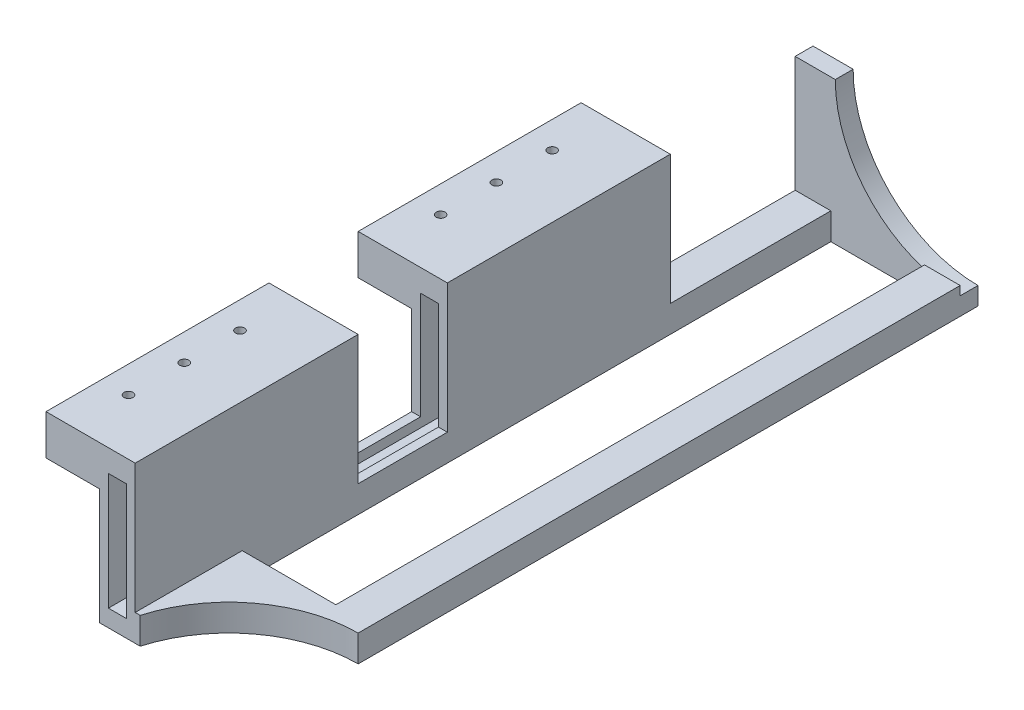
SolidWorks part; units mm, degrees
ref_plane "Alzado" through (0, 0, 0) normal (0, 0, 1) x (1, 0, 0)
ref_plane "Planta" through (0, 0, 0) normal (0, 1, 0) x (1, 0, 0)
ref_plane "Vista lateral" through (0, 0, 0) normal (1, 0, 0) x (0, 0, -1)
sketch "Croquis2" plane through (0, 0, 0) normal (0, 0, 1) x (1, 0, 0)
  line L0 (-4.5963, 11.5024) -> (-4.5963, -1.4976)
  line L1 (-8.5963, 11.5024) -> (-4.5963, 11.5024)
  line L2 (-8.5963, 11.5024) -> (-8.5963, -4.4976)
  line L3 (-8.5963, -4.4976) -> (-4.5963, -4.4976)
  line L9 (-4.5963, -4.4976) -> (9.9037, -4.4976)
  line L11 (-4.5963, -1.4976) -> (9.9037, -1.4976)
  line L12 (9.9037, -4.4976) -> (9.9037, -1.4976)
  dimension "D1" = 13
  dimension "D5" = 3
extrude "Saliente-Extruir1" add sketch "Croquis2" along normal blind 82
sketch "Croquis3" plane through (0, 11.5024, 0) normal (0, 1, 0) x (1, 0, 0)
  line L0 (-4.5963, -82) -> (-4.5963, 0) construction
  line L1 (-4.5963, -43) -> (-14.5963, -43)
  line L2 (-4.5963, -43) -> (-4.5963, -18)
  line L3 (-4.5963, -18) -> (-14.5963, -18)
  line L4 (-14.5963, -43) -> (-14.5963, -18)
  line L5 (-4.5963, -82) -> (-4.5963, 0) construction
  line L6 (-4.5963, -78) -> (-14.5963, -78)
  line L7 (-4.5963, -78) -> (-4.5963, -53)
  line L8 (-4.5963, -53) -> (-14.5963, -53)
  line L9 (-14.5963, -78) -> (-14.5963, -53)
  line L10 (9.9037, 0) -> (-4.5963, 0) construction
  line L11 (-4.5963, -82) -> (-8.5963, -82) construction
  dimension "D1" = 18
  dimension "D2" = 4
  dimension "D3" = 25
  dimension "D4" = 25
  dimension "D5" = 10
  dimension "D6" = 10
extrude "Saliente-Extruir2" add sketch "Croquis3" along normal blind 1.5
sketch "Croquis4" plane through (0, 0, 0) normal (0, 0, -1) x (-1, 0, 0)
  line L0 (-9.9037, -4.4976) -> (-9.9037, -1.4976) construction
  line L1 (8.5963, -4.4976) -> (-9.9037, -4.4976)
  line L2 (8.5963, -4.4976) -> (8.5963, 11.5024)
  line L3 (8.5963, 11.5024) -> (-9.9037, 11.5024)
  line L4 (-9.9037, -4.4976) -> (-9.9037, 11.5024)
  line L5 (4.5963, 11.5024) -> (8.5963, 11.5024) construction
extrude "Saliente-Extruir3" add sketch "Croquis4" along normal blind 2
sketch "Croquis5" plane through (0, -1.4976, 0) normal (0, 1, 0) x (1, 0, 0)
  circle A1 centre (9.9037, -82) radius 14.5
extrude "Cortar-Extruir1" cut sketch "Croquis5" against normal blind 10
sketch "Croquis9" plane through (0, 11.5024, 0) normal (0, -1, 0) x (1, 0, 0)
  line L0 (-11.5963, 59.25) -> (-11.5963, 71.75) construction
  circle A0 centre (-11.5963, 65.5) radius 0.5
  circle A1 centre (-11.5963, 59.25) radius 0.5
  circle A2 centre (-11.5963, 71.75) radius 0.5
  dimension "D1" = 1
  dimension "D3" = 1
  dimension "D4" = 1
  dimension "D2" = 6.25
extrude "Cortar-Extruir5" cut sketch "Croquis9" against normal blind 10
ref_plane "Plano2" through (0, 0, 48) normal (0, 0, -1) x (-1, 0, 0)
mirror "Simetría1" about plane through (0, 0, 48) normal (0, 0, -1) of "Cortar-Extruir5"
sketch "Croquis10" plane through (0, 0, -2) normal (0, 0, -1) x (-1, 0, 0)
  line L0 (-9.9037, 11.5024) -> (-9.9037, -4.4976) construction
  line L1 (8.5963, 11.5024) -> (-9.9037, 11.5024) construction
  line L2 (-9.9037, -2.4976) -> (-9.9037, 11.5024)
  line L3 (-9.9037, 11.5024) -> (4.0963, 11.5024)
  arc A0 (-9.9037, -2.4976) -> (4.0963, 11.5024) centre (-9.9037, 11.5024) ccw
  dimension "D1" = 14
extrude "Cortar-Extruir6" cut sketch "Croquis10" against normal blind 2
sketch "Croquis11" plane through (-8.5963, 0, 0) normal (-1, 0, 0) x (0, 0, 1)
  line L0 (82, -4.4976) -> (-2, -4.4976) construction
  line L1 (43, 11.5024) -> (53, 11.5024)
  line L2 (43, 11.5024) -> (43, -1.4976)
  line L3 (43, -1.4976) -> (53, -1.4976)
  line L4 (53, 11.5024) -> (53, -1.4976)
  line L5 (18, 11.5024) -> (0, 11.5024)
  line L6 (18, 11.5024) -> (18, -1.4976)
  line L7 (18, -1.4976) -> (0, -1.4976)
  line L8 (0, 11.5024) -> (0, -1.4976)
  line L10 (78, 11.5024) -> (86.1211, 11.5024)
  line L11 (78, 11.5024) -> (78, -8.5558)
  line L12 (78, -8.5558) -> (86.1211, -8.5558)
  line L13 (86.1211, 11.5024) -> (86.1211, -8.5558)
  line L14 (53, 13.0024) -> (53, 11.5024) construction
  line L15 (-2, -4.4976) -> (-2, 11.5024) construction
  dimension "D1" = 3
  dimension "D2" = 3
  dimension "D3" = 2
extrude "Cortar-Extruir7" cut sketch "Croquis11" against normal blind 10
sketch "Croquis12" plane through (0, 0, 78) normal (0, 0, 1) x (1, 0, 0)
  line L0 (-6.5963, -4.4976) -> (-6.5963, 12.4214) construction
  line L2 (32.2747, 11.5024) -> (-11.4673, 11.5024) construction
  line L3 (-4.5963, 13.0024) -> (-4.5963, -1.4976) construction
  line L4 (-5.5963, -2.5786) -> (-7.5963, -2.5786)
  line L5 (-5.5963, -2.5786) -> (-5.5963, 10.5024)
  line L6 (-5.5963, 10.5024) -> (-7.5963, 10.5024)
  line L7 (-7.5963, -2.5786) -> (-7.5963, 10.5024)
  line L8 (-5.5963, -2.5786) -> (-7.5963, 10.5024) construction
  line L9 (-5.5963, 10.5024) -> (-7.5963, -2.5786) construction
  point P6 (-6.5963, 3.9619)
  dimension "D1" = 1
  dimension "D2" = 1
  dimension "D3" = 2
extrude "Cortar-Extruir8" cut sketch "Croquis12" against normal blind 60
sketch "Croquis13" plane through (0, -4.4976, 0) normal (0, -1, 0) x (1, 0, 0)
  line L0 (0.6537, -2) -> (0.6537, 68) construction
  line L1 (9.9037, -2) -> (-8.5963, -2) construction
  line L2 (-8.5963, 78) -> (-8.5963, -2) construction
  line L3 (5.9037, 66) -> (-4.5963, 66)
  line L4 (5.9037, 66) -> (5.9037, 0)
  line L5 (5.9037, 0) -> (-4.5963, 0)
  line L6 (-4.5963, 66) -> (-4.5963, 0)
  line L7 (5.9037, 66) -> (-4.5963, 0) construction
  line L8 (5.9037, 0) -> (-4.5963, 66) construction
  point P4 (0.6537, 33)
  dimension "D1" = 70
  dimension "D2" = 2
  dimension "D3" = 4
extrude "Cortar-Extruir9" cut sketch "Croquis13" against normal blind 12
sketch "Croquis14" plane through (0, 11.5024, 0) normal (0, -1, 0) x (1, 0, 0)
  line L1 (-14.5963, 53) -> (-8.5963, 53)
  line L2 (-14.5963, 53) -> (-14.5963, 78)
  line L3 (-14.5963, 78) -> (-8.5963, 78)
  line L4 (-8.5963, 53) -> (-8.5963, 78)
  line L5 (-14.5963, 43) -> (-8.5963, 43)
  line L6 (-14.5963, 43) -> (-14.5963, 18)
  line L7 (-14.5963, 18) -> (-8.5963, 18)
  line L8 (-8.5963, 43) -> (-8.5963, 18)
extrude "Saliente-Extruir4" add sketch "Croquis14" along normal blind 3
sketch "Croquis15" plane through (0, 11.5024, 0) normal (0, 1, 0) x (1, 0, 0)
  circle A0 centre (-11.5963, -24.25) radius 0.5
  circle A1 centre (-11.5963, -30.5) radius 0.5
  circle A2 centre (-11.5963, -36.75) radius 0.5
  circle A3 centre (-11.5963, -65.5) radius 0.5
  circle A4 centre (-11.5963, -59.25) radius 0.5
  circle A5 centre (-11.5963, -71.75) radius 0.5
extrude "Cortar-Extruir10" cut sketch "Croquis15" against normal through all
